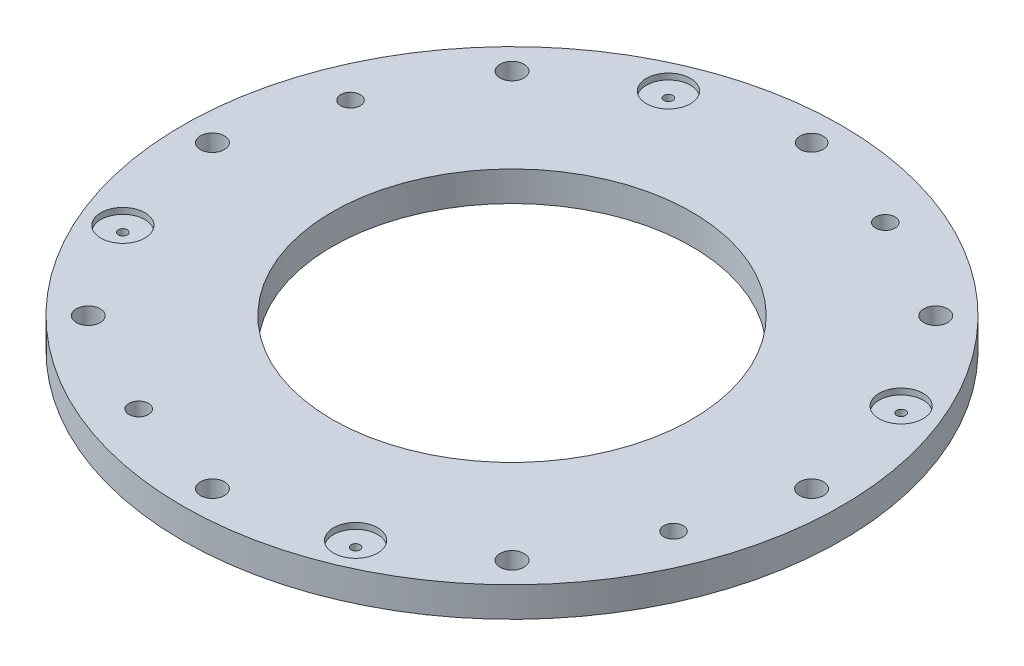
SolidWorks part; units mm, degrees
material "Aleación 6061"
ref_plane "Alzado" through (0, 0, 0) normal (0, 0, 1) x (1, 0, 0)
ref_plane "Planta" through (0, 0, 0) normal (0, 1, 0) x (1, 0, 0)
ref_plane "Vista lateral" through (0, 0, 0) normal (1, 0, 0) x (0, 0, -1)
sketch "Croquis1" plane through (0, 0, 0) normal (0, 1, 0) x (1, 0, 0)
  circle A0 centre (0, 0) radius 110
  dimension "D1" = 220
extrude "Saliente-Extruir1" add sketch "Croquis1" along normal blind 10
sketch "Croquis2" plane through (0, 10, 0) normal (0, 1, 0) x (1, 0, 0)
  line L0 (0, 110) -> (0, -110) construction
  line L1 (-110, 0) -> (110, 0) construction
  circle A0 centre (0, 0) radius 110 construction
  circle A1 centre (0, 100) radius 3.8621
  circle A2 centre (-100, 0) radius 4
  circle A3 centre (0, -100) radius 4
  circle A4 centre (100, 0) radius 4
  circle A6 centre (-70.7107, 70.7107) radius 4
  circle A7 centre (0, 100) radius 4
  circle A8 centre (70.7107, 70.7107) radius 4
  circle A9 centre (100, 0) radius 4
  circle A10 centre (70.7107, -70.7107) radius 4
  circle A11 centre (0, -100) radius 4
  circle A12 centre (-70.7107, -70.7107) radius 4
  point P35 (0, 0)
  dimension "D1" = 10
  dimension "D5" = 8
  dimension "D2" = 10
  dimension "D3" = 10
  dimension "D4" = 10
extrude "Cortar-Extruir1" cut sketch "Croquis2" against normal blind 10
sketch "Croquis3" plane through (0, 10, 0) normal (0, 1, 0) x (1, 0, 0)
  circle A0 centre (0, 0) radius 60
  dimension "D1" = 120
extrude "Cortar-Extruir2" cut sketch "Croquis3" against normal blind 10
sketch "Croquis4" plane through (0, 10, 0) normal (0, 1, 0) x (1, 0, 0)
  circle A0 centre (89.2547, -35.3496) radius 3.25
  circle A1 centre (-35.3496, -89.2547) radius 3.25
  circle A2 centre (-89.2547, 35.3496) radius 3.25
  circle A3 centre (35.3496, 89.2547) radius 3.25
  dimension "D1" = 6.5
extrude "Cortar-Extruir3" cut sketch "Croquis4" against normal blind 10
sketch "Croquis5" plane through (0, 10, 0) normal (0, 1, 0) x (1, 0, 0)
  circle A0 centre (91.0465, 38.8422) radius 7.35
  circle A1 centre (38.8422, -91.0465) radius 7.35
  circle A2 centre (-91.0465, -38.8422) radius 7.35
  circle A3 centre (-38.8422, 91.0465) radius 7.35
  point P12 (0, 0)
  dimension "D2" = 14.7
  dimension "D1" = 4
extrude "Cortar-Extruir4" cut sketch "Croquis5" against normal blind 2
sketch "Croquis7" plane through (0, 10, 0) normal (0, 1, 0) x (1, 0, 0)
  circle A0 centre (-38.8422, 91.0465) radius 1.5
  circle A1 centre (91.0465, 38.8422) radius 1.5
  circle A2 centre (38.8422, -91.0465) radius 1.5
  circle A3 centre (-91.0465, -38.8422) radius 1.5
  dimension "D1" = 3
extrude "Cortar-Extruir5" cut sketch "Croquis7" against normal blind 10
